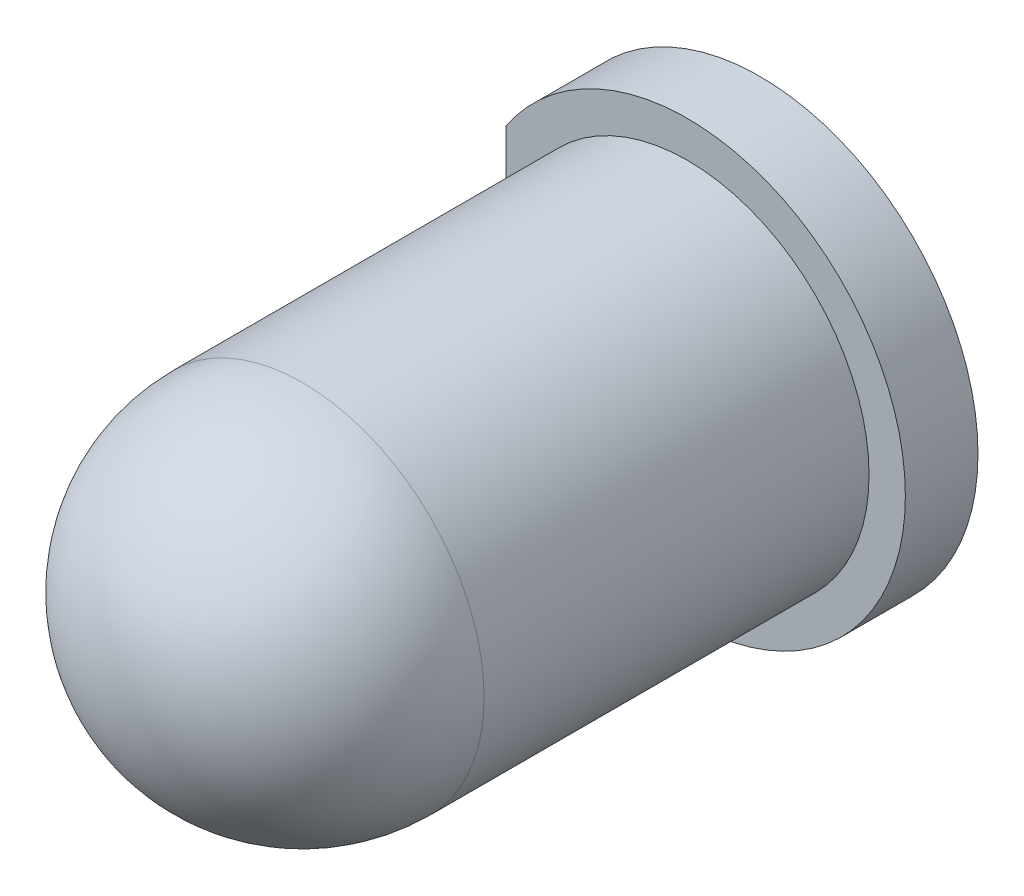
SolidWorks part; units mm, degrees
ref_plane "Plano frontal" through (0, 0, 0) normal (0, 0, 1) x (1, 0, 0)
ref_plane "Plano superior" through (0, 0, 0) normal (0, 1, 0) x (1, 0, 0)
ref_plane "Plano direito" through (0, 0, 0) normal (1, 0, 0) x (0, 0, -1)
sketch "Esboço1" plane through (0, 0, 0) normal (0, 0, 1) x (1, 0, 0)
  circle A0 centre (0, 0) radius 3
  dimension "D1" = 6
extrude "Ressalto-extrusão1" add sketch "Esboço1" along normal blind 1
sketch "Esboço3" plane through (0, 0, 0) normal (1, 0, 0) x (0, 0, -1)
  line L0 (-1, 0) -> (-8.8, 0)
  line L1 (-1, 3) -> (-1, -3) construction
  line L2 (-6.3, 2.5) -> (-1, 2.5)
  line L3 (-1, 0) -> (-1, 2.5)
  arc A0 (-8.8, 0) -> (-6.3, 2.5) centre (-6.3, 0) cw
  dimension "D1" = 2.5
  dimension "D2" = 7.8
revolve "Revolução1" add sketch "Esboço3" angle 360 about L0
sketch "Esboço4" plane through (0, 0, 0) normal (0, 0, -1) x (-1, 0, 0)
  line L0 (2.5, 1.6583) -> (2.5, -1.6583)
  circle A0 centre (0, 0) radius 3 construction
  arc A1 (2.5, -1.6583) -> (2.5, 1.6583) centre (0, 0) ccw
  circle A2 centre (0, 0) radius 2.5 construction
extrude "Corte-extrusão1" cut sketch "Esboço4" against normal up to surface (1 mm away) up to face at (2.5, 0, 1)
sketch "Esboço5" plane through (0, 0, 0) normal (0, 0, -1) x (-1, 0, 0)
  line L0 (-1.12, 0) -> (1.12, 0) construction
  line L1 (-1.6, -0.24) -> (-1.12, -0.24)
  line L2 (-1.6, -0.24) -> (-1.6, 0.24)
  line L3 (-1.6, 0.24) -> (-1.12, 0.24)
  line L4 (-1.12, -0.24) -> (-1.12, 0.24)
  line L5 (1.12, -0.24) -> (1.6, -0.24)
  line L6 (1.12, -0.24) -> (1.12, 0.24)
  line L7 (1.12, 0.24) -> (1.6, 0.24)
  line L8 (1.6, -0.24) -> (1.6, 0.24)
  dimension "D1" = 3.2
  dimension "D2" = 0.48
